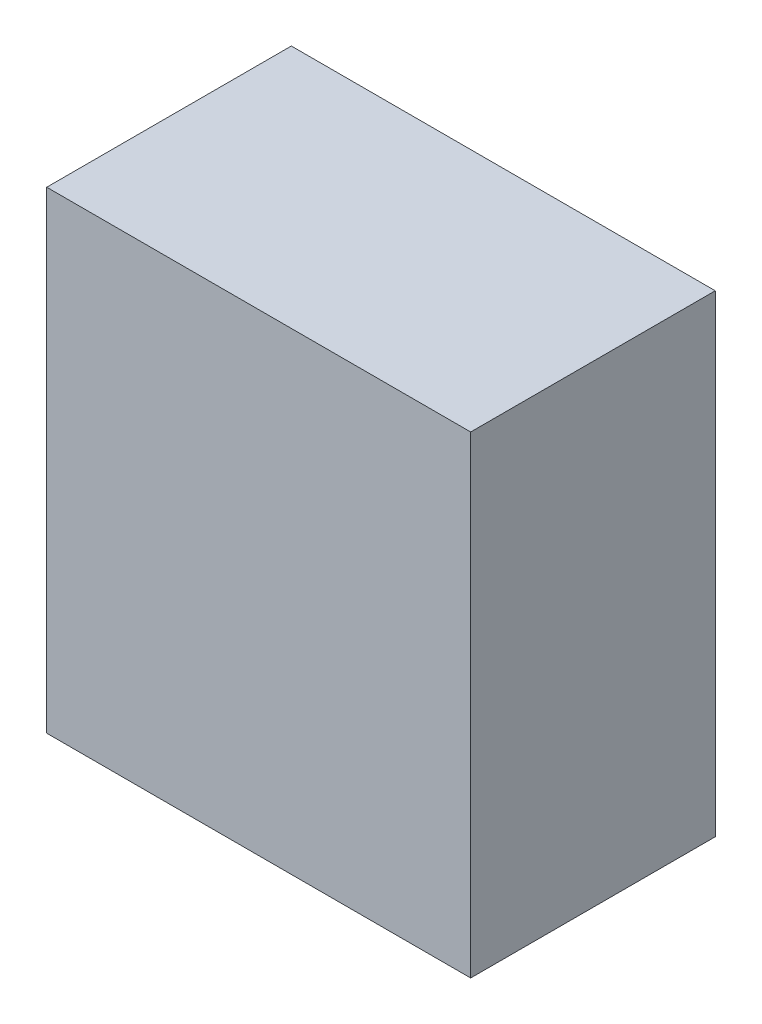
SolidWorks part; units mm, degrees
ref_plane "Plan de face" through (0, 0, 0) normal (0, 0, 1) x (1, 0, 0)
ref_plane "Plan de dessus" through (0, 0, 0) normal (0, 1, 0) x (1, 0, 0)
ref_plane "Plan de droite" through (0, 0, 0) normal (1, 0, 0) x (0, 0, -1)
sketch "Esquisse1" plane through (0, 0, 0) normal (0, 0, 1) x (1, 0, 0)
  line L1 (-26, 29) -> (26, 29)
  line L2 (-26, 29) -> (-26, -29)
  line L3 (-26, -29) -> (26, -29)
  line L4 (26, 29) -> (26, -29)
  line L5 (-26, 29) -> (26, -29) construction
  line L6 (-26, -29) -> (26, 29) construction
  point P0 (0, 0)
  dimension "D1" = 58
  dimension "D2" = 52
extrude "Boss.-Extru.1" add sketch "Esquisse1" along normal blind 30
